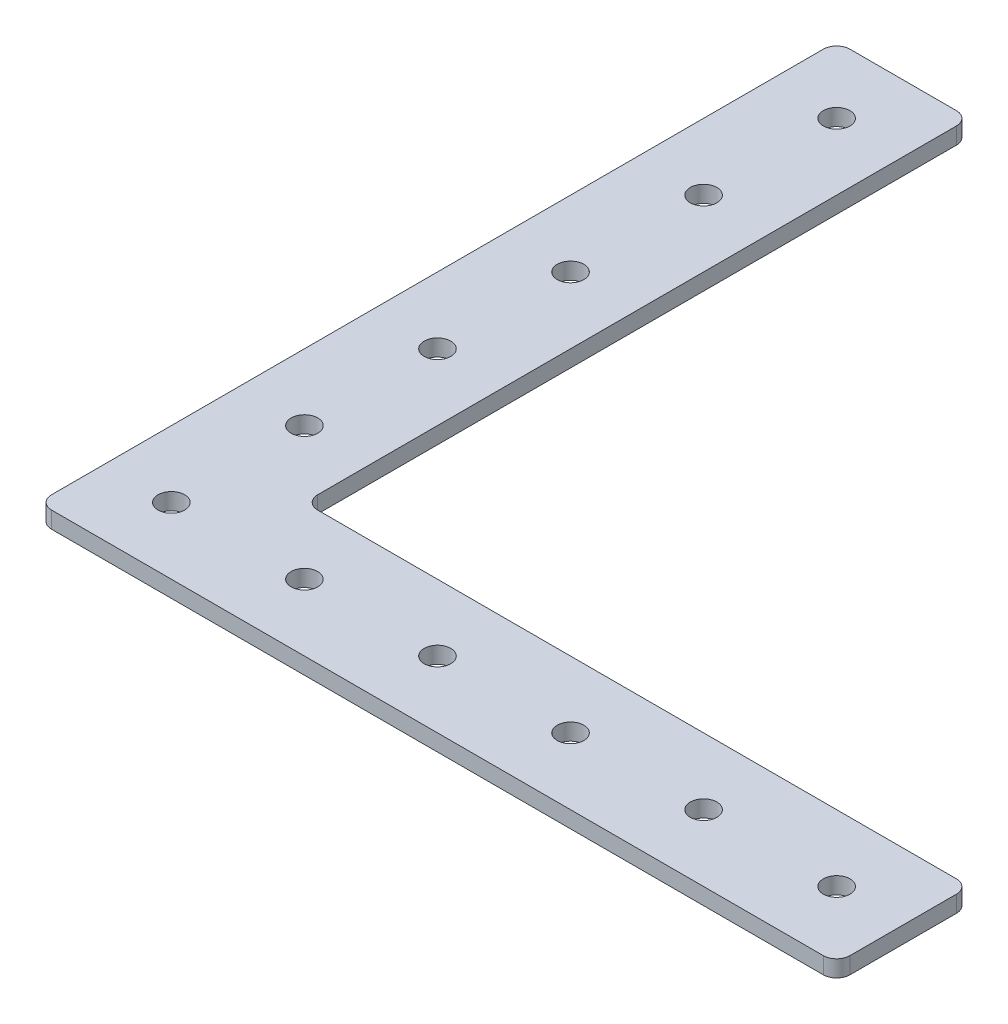
SolidWorks part; units mm, degrees
material "6061 Alloy"
ref_plane "Front Plane" through (0, 0, 0) normal (0, 0, 1) x (1, 0, 0)
ref_plane "Top Plane" through (0, 0, 0) normal (0, 1, 0) x (1, 0, 0)
ref_plane "Right Plane" through (0, 0, 0) normal (1, 0, 0) x (0, 0, -1)
sketch "Sketch1" plane through (0, 0, 0) normal (0, 1, 0) x (1, 0, 0)
  line L0 (0, -2.54) -> (0, -149.86)
  line L1 (2.54, -152.4) -> (149.86, -152.4)
  line L2 (2.54, 0) -> (22.86, 0)
  line L3 (25.4, -2.54) -> (25.4, -124.46)
  line L4 (152.4, -149.86) -> (152.4, -129.54)
  line L5 (27.94, -127) -> (149.86, -127)
  arc A0 (0, -149.86) -> (2.54, -152.4) centre (2.54, -149.86) ccw
  arc A1 (149.86, -152.4) -> (152.4, -149.86) centre (149.86, -149.86) ccw
  arc A2 (152.4, -129.54) -> (149.86, -127) centre (149.86, -129.54) ccw
  arc A3 (25.4, -124.46) -> (27.94, -127) centre (27.94, -124.46) ccw
  arc A4 (22.86, 0) -> (25.4, -2.54) centre (22.86, -2.54) cw
  arc A5 (0, -2.54) -> (2.54, 0) centre (2.54, -2.54) cw
  point P9 (0, -152.4)
  point P12 (152.4, -152.4)
  point P21 (0, 0)
  dimension "D3" = 2.54
  dimension "D1" = 152.4
  dimension "D2" = 152.4
extrude "Boss-Extrude1" add sketch "Sketch1" along normal blind 3.175
sketch "Sketch2" plane through (0, 3.175, 0) normal (0, 1, 0) x (1, 0, 0)
  line L0 (22.86, 0) -> (2.54, 0) construction
  line L1 (12.7, 0) -> (12.7, -35.9172) construction
  circle A0 centre (12.7, -12.7) radius 2.54
  dimension "D1" = 12.7
  dimension "D2" = 5.08
extrude "Cut-Extrude1" cut sketch "Sketch2" against normal up to surface (3.175 mm away) up to face at (59.2667, 0, 93.1333)
pattern_linear "LPattern1" count 6 spacing 25.4 along (0, 0, 1) of "Cut-Extrude1"
sketch "Sketch3" plane through (0, 3.175, 0) normal (0, 1, 0) x (1, 0, 0)
  line L0 (12.7, 0) -> (12.7, -152.4) construction
  line L1 (22.86, 0) -> (2.54, 0) construction
  line L2 (2.54, -152.4) -> (149.86, -152.4) construction
  line L3 (152.4, -139.7) -> (0, -139.7) construction
  line L4 (152.4, -149.86) -> (152.4, -129.54) construction
  line L5 (0, -2.54) -> (0, -149.86) construction
  circle A0 centre (139.7, -139.7) radius 2.54
  dimension "D1" = 12.7
extrude "Cut-Extrude2" cut sketch "Sketch3" against normal up to surface (3.175 mm away) up to face at (12.7, 0, 40.64)
pattern_linear "LPattern2" count 5 spacing 25.4 along (-1, 0, 0) of "Cut-Extrude2"
